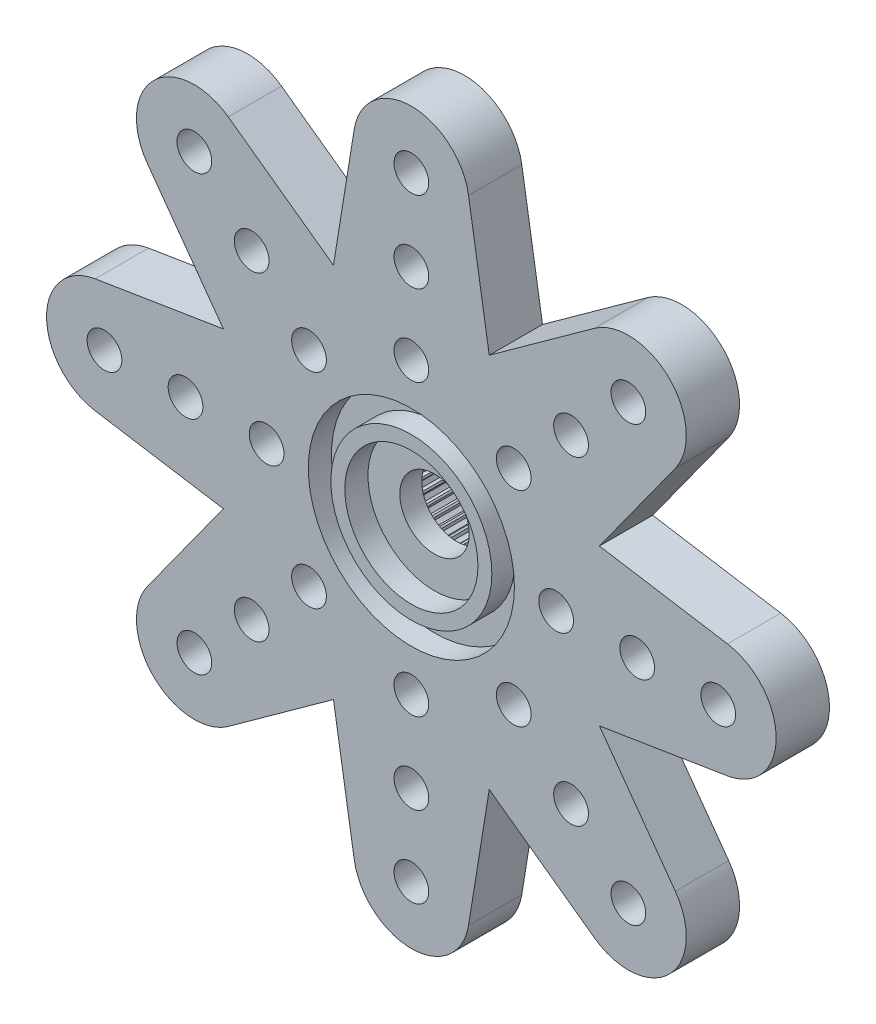
SolidWorks part; units mm, degrees
ref_plane "Plan de face" through (0, 0, 0) normal (0, 0, 1) x (1, 0, 0)
ref_plane "Plan de dessus" through (0, 0, 0) normal (0, 1, 0) x (1, 0, 0)
ref_plane "Plan de droite" through (0, 0, 0) normal (1, 0, 0) x (0, 0, -1)
sketch "Esquisse1" plane through (0, 0, 0) normal (0, 0, 1) x (1, 0, 0)
  line L2 (-13.6493, 2.4679) -> (-8.1183, 3.3627)
  line L3 (-13.6493, -2.4679) -> (-8.1183, -3.3627)
  line L5 (13.6493, -2.4679) -> (8.1183, -3.3627)
  line L6 (13.6493, 2.4679) -> (8.1183, 3.3627)
  line L7 (2.4679, 13.6493) -> (3.3627, 8.1183)
  line L8 (-2.4679, 13.6493) -> (-3.3627, 8.1183)
  line L9 (-2.4679, -13.6493) -> (-3.3627, -8.1183)
  line L10 (2.4679, -13.6493) -> (3.3627, -8.1183)
  line L17 (-7.9064, 11.3966) -> (-3.3627, 8.1183)
  line L18 (-11.3966, 7.9064) -> (-8.1183, 3.3627)
  line L19 (7.9064, -11.3966) -> (3.3627, -8.1183)
  line L20 (11.3966, -7.9064) -> (8.1183, -3.3627)
  line L21 (11.3966, 7.9064) -> (8.1183, 3.3627)
  line L22 (7.9064, 11.3966) -> (3.3627, 8.1183)
  line L23 (-11.3966, -7.9064) -> (-8.1183, -3.3627)
  line L24 (-7.9064, -11.3966) -> (-3.3627, -8.1183)
  arc A3 (-13.6493, 2.4679) -> (-13.6493, -2.4679) centre (-13.25, 0) ccw
  arc A4 (13.6493, 2.4679) -> (13.6493, -2.4679) centre (13.25, 0) cw
  arc A6 (2.4679, 13.6493) -> (-2.4679, 13.6493) centre (0, 13.25) ccw
  arc A7 (2.4679, -13.6493) -> (-2.4679, -13.6493) centre (0, -13.25) cw
  arc A8 (-7.9064, 11.3966) -> (-11.3966, 7.9064) centre (-9.3692, 9.3692) ccw
  arc A9 (11.3966, -7.9064) -> (7.9064, -11.3966) centre (9.3692, -9.3692) cw
  arc A10 (11.3966, 7.9064) -> (7.9064, 11.3966) centre (9.3692, 9.3692) ccw
  arc A11 (-7.9064, -11.3966) -> (-11.3966, -7.9064) centre (-9.3692, -9.3692) cw
  dimension "D2" = 2.5
  dimension "D4" = 2
  dimension "D3" = 26.5
extrude "Boss.-Extru.1" add sketch "Esquisse1" along normal blind 2.3
sketch "Esquisse2" plane through (0, 0, 2.3) normal (0, 0, 1) x (1, 0, 0)
  circle A0 centre (0, 0) radius 4.45
  dimension "D1" = 8.9
extrude "Enlèv. mat.-Extru.1" cut sketch "Esquisse2" against normal blind 1
sketch "Esquisse3" plane through (0, 0, 1.3) normal (0, 0, 1) x (1, 0, 0)
  circle A0 centre (0, 0) radius 2.875
  circle A1 centre (0, 0) radius 3.475
  dimension "D1" = 5.75
  dimension "D2" = 0.6
extrude "Boss.-Extru.2" add sketch "Esquisse3" along normal up to surface (1 mm away) up to face at (4.45, 0, 2.3)
sketch "Esquisse4" plane through (0, 0, 0) normal (0, 0, -1) x (-1, 0, 0)
  circle A0 centre (0, 0) radius 4.4
  dimension "D1" = 8.8
extrude "Boss.-Extru.3" add sketch "Esquisse4" along normal blind 3
sketch "Esquisse5" plane through (0, 0, 1.3) normal (0, 0, 1) x (1, 0, 0)
  circle A0 centre (0, 0) radius 1.5
  dimension "D1" = 3
extrude "Enlèv. mat.-Extru.2" cut sketch "Esquisse5" against normal through all
sketch "Esquisse6" plane through (0, 0, -3) normal (0, 0, -1) x (-1, 0, 0)
  line L0 (-0.1143, 2.9978) -> (-0.0406, 2.8652)
  line L1 (0.0406, 2.8652) -> (0.1143, 2.9978)
  line L2 (0, 2.8652) -> (0, 0) construction
  line L3 (-0.0406, 2.8652) -> (0.0406, 2.8652)
  line L4 (0.439, 2.8316) -> (0.5304, 2.9527)
  line L5 (0.3041, 2.9846) -> (0.3585, 2.8429)
  line L6 (0.3585, 2.8429) -> (0.439, 2.8316)
  line L7 (0.8288, 2.743) -> (0.9362, 2.8502)
  line L8 (0.7165, 2.9132) -> (0.7507, 2.7654)
  line L9 (0.7507, 2.7654) -> (0.8288, 2.743)
  line L10 (1.2025, 2.6009) -> (1.3237, 2.6922)
  line L11 (1.1149, 2.7851) -> (1.1283, 2.634)
  line L12 (1.1283, 2.634) -> (1.2025, 2.6009)
  line L13 (1.5527, 2.4083) -> (1.6855, 2.4817)
  line L14 (1.4917, 2.6029) -> (1.4839, 2.4513)
  line L15 (1.4839, 2.4513) -> (1.5527, 2.4083)
  line L16 (1.8728, 2.1687) -> (2.0145, 2.223)
  line L17 (1.8394, 2.3699) -> (1.8106, 2.2209)
  line L18 (1.8106, 2.2209) -> (1.8728, 2.1687)
  line L19 (2.1564, 1.887) -> (2.3043, 1.921)
  line L20 (2.1514, 2.0909) -> (2.1021, 1.9473)
  line L21 (2.1021, 1.9473) -> (2.1564, 1.887)
  line L22 (2.398, 1.5685) -> (2.5492, 1.5816)
  line L23 (2.4214, 1.7711) -> (2.3526, 1.6358)
  line L24 (2.3526, 1.6358) -> (2.398, 1.5685)
  line L25 (2.593, 1.2195) -> (2.7445, 1.2114)
  line L26 (2.6443, 1.4169) -> (2.5574, 1.2925)
  line L27 (2.5574, 1.2925) -> (2.593, 1.2195)
  line L28 (2.7375, 0.8468) -> (2.8864, 0.8177)
  line L29 (2.8158, 1.0351) -> (2.7124, 0.924)
  line L30 (2.7124, 0.924) -> (2.7375, 0.8468)
  line L31 (2.8287, 0.4575) -> (2.9721, 0.408)
  line L32 (2.9324, 0.6331) -> (2.8146, 0.5375)
  line L33 (2.8146, 0.5375) -> (2.8287, 0.4575)
  line L34 (2.8648, 0.0594) -> (3, -0.0096)
  line L35 (2.992, 0.2188) -> (2.862, 0.1406)
  line L36 (2.862, 0.1406) -> (2.8648, 0.0594)
  line L37 (2.8452, -0.3399) -> (2.9695, -0.427)
  line L38 (2.9933, -0.1997) -> (2.8537, -0.2591)
  line L39 (2.8537, -0.2591) -> (2.8452, -0.3399)
  line L40 (2.7702, -0.7325) -> (2.8811, -0.8361)
  line L41 (2.9364, -0.6144) -> (2.7899, -0.6537)
  line L42 (2.7899, -0.6537) -> (2.7702, -0.7325)
  line L43 (2.6413, -1.111) -> (2.7367, -1.229)
  line L44 (2.8223, -1.017) -> (2.6717, -1.0357)
  line L45 (2.6717, -1.0357) -> (2.6413, -1.111)
  line L46 (2.461, -1.4677) -> (2.5391, -1.5979)
  line L47 (2.6533, -1.3999) -> (2.5016, -1.3974)
  line L48 (2.5016, -1.3974) -> (2.461, -1.4677)
  line L49 (2.2328, -1.796) -> (2.292, -1.9357)
  line L50 (2.4327, -1.7556) -> (2.2828, -1.732)
  line L51 (2.2828, -1.732) -> (2.2328, -1.796)
  line L52 (1.9611, -2.0892) -> (2.0003, -2.2358)
  line L53 (2.1647, -2.0771) -> (2.0195, -2.0328)
  line L54 (2.0195, -2.0328) -> (1.9611, -2.0892)
  line L55 (1.6512, -2.3418) -> (1.6696, -2.4925)
  line L56 (1.8545, -2.3581) -> (1.7169, -2.2941)
  line L57 (1.7169, -2.2941) -> (1.6512, -2.3418)
  line L58 (1.3093, -2.5488) -> (1.3065, -2.7006)
  line L59 (1.5083, -2.5933) -> (1.381, -2.5107)
  line L60 (1.381, -2.5107) -> (1.3093, -2.5488)
  line L61 (0.9418, -2.7063) -> (0.9179, -2.8561)
  line L62 (1.1327, -2.7779) -> (1.0181, -2.6785)
  line L63 (1.0181, -2.6785) -> (0.9418, -2.7063)
  line L64 (0.556, -2.811) -> (0.5115, -2.9561)
  line L65 (0.7351, -2.9086) -> (0.6354, -2.7941)
  line L66 (0.6354, -2.7941) -> (0.556, -2.811)
  line L67 (0.1594, -2.861) -> (0.0951, -2.9985)
  line L68 (0.3231, -2.9825) -> (0.2404, -2.8553)
  line L69 (0.2404, -2.8553) -> (0.1594, -2.861)
  line L70 (-0.2404, -2.8553) -> (-0.3231, -2.9825)
  line L71 (-0.0951, -2.9985) -> (-0.1594, -2.861)
  line L72 (-0.1594, -2.861) -> (-0.2404, -2.8553)
  line L73 (-0.6354, -2.7941) -> (-0.7351, -2.9086)
  line L74 (-0.5115, -2.9561) -> (-0.556, -2.811)
  line L75 (-0.556, -2.811) -> (-0.6354, -2.7941)
  line L76 (-1.0181, -2.6785) -> (-1.1327, -2.7779)
  line L77 (-0.9179, -2.8561) -> (-0.9418, -2.7063)
  line L78 (-0.9418, -2.7063) -> (-1.0181, -2.6785)
  line L79 (-1.381, -2.5107) -> (-1.5083, -2.5933)
  line L80 (-1.3065, -2.7006) -> (-1.3093, -2.5488)
  line L81 (-1.3093, -2.5488) -> (-1.381, -2.5107)
  line L82 (-1.7169, -2.2941) -> (-1.8545, -2.3581)
  line L83 (-1.6696, -2.4925) -> (-1.6512, -2.3418)
  line L84 (-1.6512, -2.3418) -> (-1.7169, -2.2941)
  line L85 (-2.0195, -2.0328) -> (-2.1647, -2.0771)
  line L86 (-2.0003, -2.2358) -> (-1.9611, -2.0892)
  line L87 (-1.9611, -2.0892) -> (-2.0195, -2.0328)
  line L88 (-2.2828, -1.732) -> (-2.4327, -1.7556)
  line L89 (-2.292, -1.9357) -> (-2.2328, -1.796)
  line L90 (-2.2328, -1.796) -> (-2.2828, -1.732)
  line L91 (-2.5016, -1.3974) -> (-2.6533, -1.3999)
  line L92 (-2.5391, -1.5979) -> (-2.461, -1.4677)
  line L93 (-2.461, -1.4677) -> (-2.5016, -1.3974)
  line L94 (-2.6717, -1.0357) -> (-2.8223, -1.017)
  line L95 (-2.7367, -1.229) -> (-2.6413, -1.111)
  line L96 (-2.6413, -1.111) -> (-2.6717, -1.0357)
  line L97 (-2.7899, -0.6537) -> (-2.9364, -0.6144)
  line L98 (-2.8811, -0.8361) -> (-2.7702, -0.7325)
  line L99 (-2.7702, -0.7325) -> (-2.7899, -0.6537)
  line L100 (-2.8537, -0.2591) -> (-2.9933, -0.1997)
  line L101 (-2.9695, -0.427) -> (-2.8452, -0.3399)
  line L102 (-2.8452, -0.3399) -> (-2.8537, -0.2591)
  line L103 (-2.862, 0.1406) -> (-2.992, 0.2188)
  line L104 (-3, -0.0096) -> (-2.8648, 0.0594)
  line L105 (-2.8648, 0.0594) -> (-2.862, 0.1406)
  line L106 (-2.8146, 0.5375) -> (-2.9324, 0.6331)
  line L107 (-2.9721, 0.408) -> (-2.8287, 0.4575)
  line L108 (-2.8287, 0.4575) -> (-2.8146, 0.5375)
  line L109 (-2.7124, 0.924) -> (-2.8158, 1.0351)
  line L110 (-2.8864, 0.8177) -> (-2.7375, 0.8468)
  line L111 (-2.7375, 0.8468) -> (-2.7124, 0.924)
  line L112 (-2.5574, 1.2925) -> (-2.6443, 1.4169)
  line L113 (-2.7445, 1.2114) -> (-2.593, 1.2195)
  line L114 (-2.593, 1.2195) -> (-2.5574, 1.2925)
  line L115 (-2.3526, 1.6358) -> (-2.4214, 1.7711)
  line L116 (-2.5492, 1.5816) -> (-2.398, 1.5685)
  line L117 (-2.398, 1.5685) -> (-2.3526, 1.6358)
  line L118 (-2.1021, 1.9473) -> (-2.1514, 2.0909)
  line L119 (-2.3043, 1.921) -> (-2.1564, 1.887)
  line L120 (-2.1564, 1.887) -> (-2.1021, 1.9473)
  line L121 (-1.8106, 2.2209) -> (-1.8394, 2.3699)
  line L122 (-2.0145, 2.223) -> (-1.8728, 2.1687)
  line L123 (-1.8728, 2.1687) -> (-1.8106, 2.2209)
  line L124 (-1.4839, 2.4513) -> (-1.4917, 2.6029)
  line L125 (-1.6855, 2.4817) -> (-1.5527, 2.4083)
  line L126 (-1.5527, 2.4083) -> (-1.4839, 2.4513)
  line L127 (-1.1283, 2.634) -> (-1.1149, 2.7851)
  line L128 (-1.3237, 2.6922) -> (-1.2025, 2.6009)
  line L129 (-1.2025, 2.6009) -> (-1.1283, 2.634)
  line L130 (-0.7507, 2.7654) -> (-0.7165, 2.9132)
  line L131 (-0.9362, 2.8502) -> (-0.8288, 2.743)
  line L132 (-0.8288, 2.743) -> (-0.7507, 2.7654)
  line L133 (-0.3585, 2.8429) -> (-0.3041, 2.9846)
  line L134 (-0.5304, 2.9527) -> (-0.439, 2.8316)
  line L135 (-0.439, 2.8316) -> (-0.3585, 2.8429)
  circle A0 centre (0, 0) radius 3
  point P187 (0, 0)
  dimension "D1" = 6
  dimension "D2" = 45
extrude "Enlèv. mat.-Extru.3" cut sketch "Esquisse6" against normal blind 3.35
sketch "Esquisse7" plane through (0, 0, 2.3) normal (0, 0, 1) x (1, 0, 0)
  circle A0 centre (-13.25, 0) radius 0.75
  circle A20 centre (-9.75, 0) radius 0.75
  circle A21 centre (-9.3692, 9.3692) radius 0.75
  circle A22 centre (-6.25, 0) radius 0.75
  circle A23 centre (-6.8943, 6.8943) radius 0.75
  circle A24 centre (-4.4194, 4.4194) radius 0.75
  circle A25 centre (0, 13.25) radius 0.75
  circle A26 centre (0, 9.75) radius 0.75
  circle A27 centre (0, 6.25) radius 0.75
  circle A28 centre (9.3692, 9.3692) radius 0.75
  circle A29 centre (6.8943, 6.8943) radius 0.75
  circle A30 centre (4.4194, 4.4194) radius 0.75
  circle A31 centre (13.25, 0) radius 0.75
  circle A32 centre (9.75, 0) radius 0.75
  circle A33 centre (6.25, 0) radius 0.75
  circle A34 centre (9.3692, -9.3692) radius 0.75
  circle A35 centre (6.8943, -6.8943) radius 0.75
  circle A36 centre (4.4194, -4.4194) radius 0.75
  circle A37 centre (0, -13.25) radius 0.75
  circle A38 centre (0, -9.75) radius 0.75
  circle A39 centre (0, -6.25) radius 0.75
  circle A40 centre (-9.3692, -9.3692) radius 0.75
  circle A41 centre (-6.8943, -6.8943) radius 0.75
  circle A42 centre (-4.4194, -4.4194) radius 0.75
  point P52 (0, 0)
  dimension "D1" = 1.5
  dimension "D2" = 3
extrude "Enlèv. mat.-Extru.4" cut sketch "Esquisse7" against normal blind 3.35
